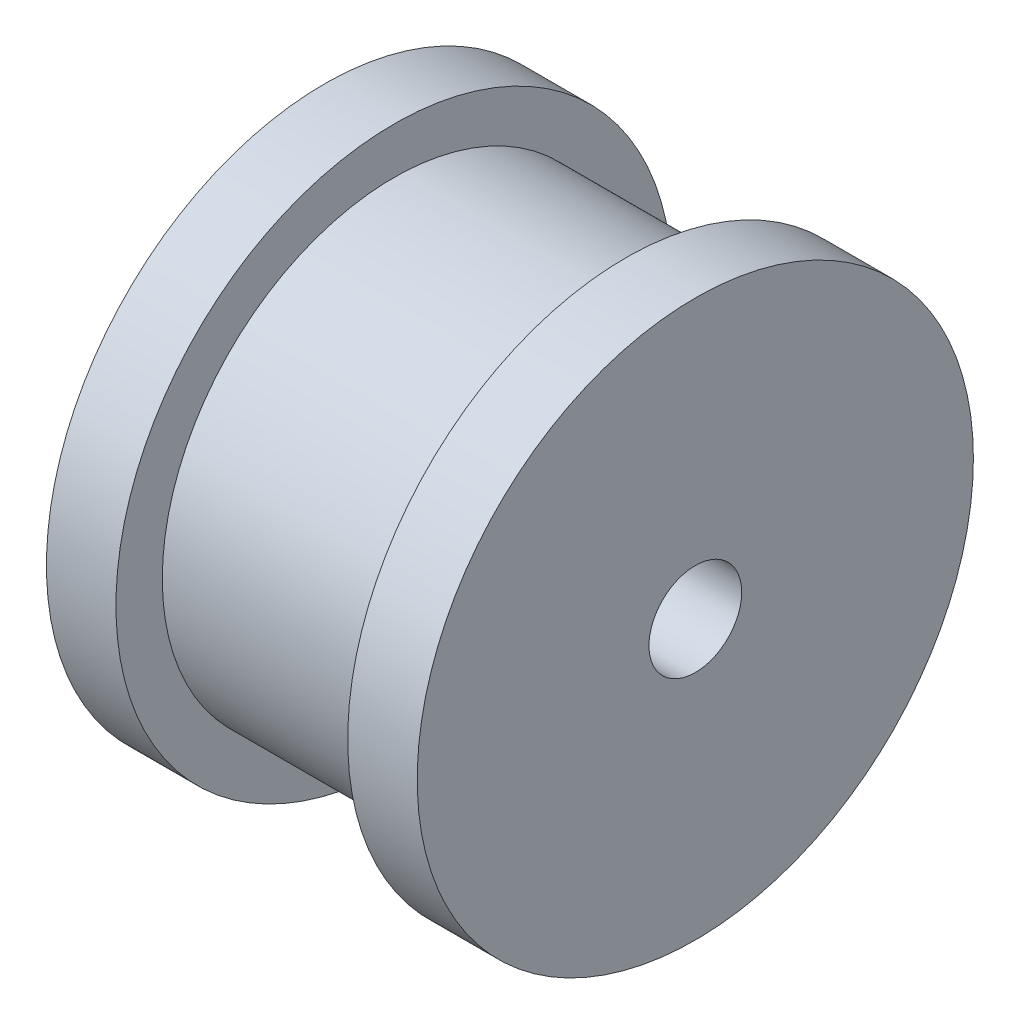
SolidWorks part; units mm, degrees
ref_plane "前视基准面" through (0, 0, 0) normal (0, 0, 1) x (1, 0, 0)
ref_plane "上视基准面" through (0, 0, 0) normal (0, 1, 0) x (1, 0, 0)
ref_plane "右视基准面" through (0, 0, 0) normal (1, 0, 0) x (0, 0, -1)
other "Configuration Table"
sketch "草图2" plane through (0, 0, 0) normal (1, 0, 0) x (0, 0, -1)
  circle A0 centre (0, 0) radius 12
extrude "凸台-拉伸1" add sketch "草图2" along normal mid plane 16
sketch "草图3" plane through (0, 0, 0) normal (1, 0, 0) x (0, 0, -1)
  circle A1 centre (0, 0) radius 12 construction
  circle A2 centre (0, 0) radius 10
  circle A3 centre (0, 0) radius 10
  circle A4 centre (0, 0) radius 12
  dimension "D1" = 2
extrude "切除-拉伸1" cut sketch "草图3" against normal mid plane 10
sketch "草图4" plane through (0, 0, 0) normal (1, 0, 0) x (0, 0, -1)
  circle A0 centre (0, 0) radius 2
extrude "切除-拉伸2" cut sketch "草图4" against normal through all both and the other way through all
